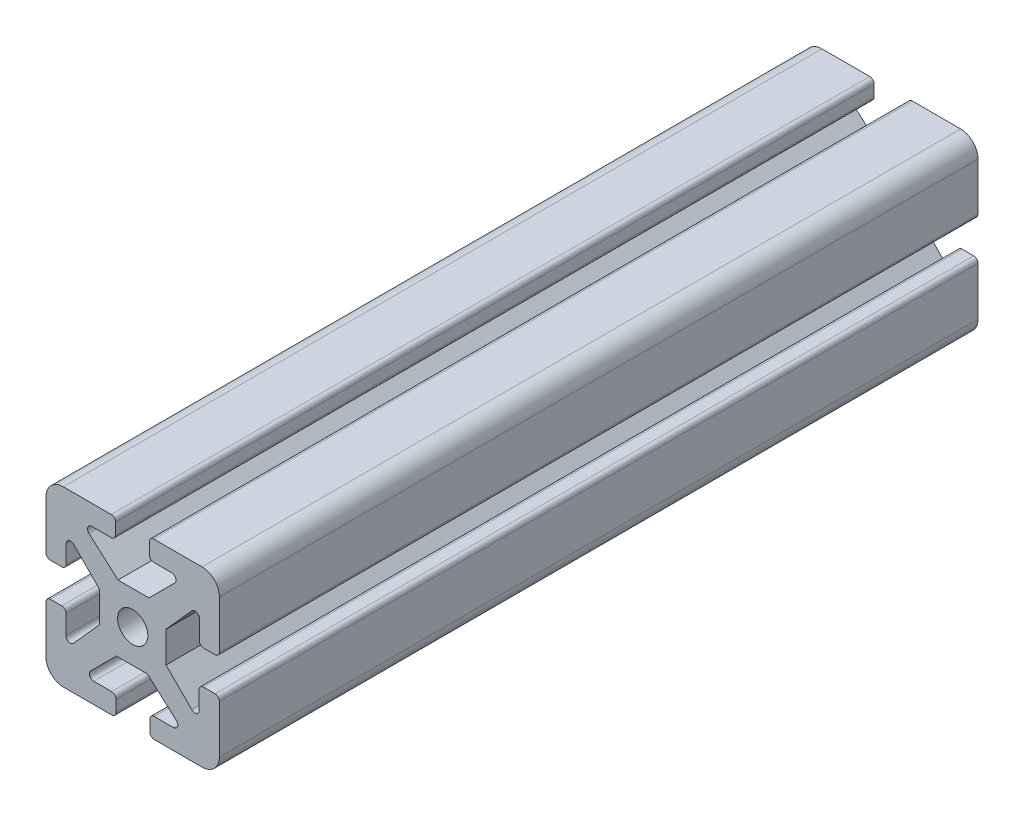
SolidWorks part; units mm, degrees
ref_plane "Front Plane" through (0, 0, 0) normal (0, 0, 1) x (1, 0, 0)
ref_plane "Top Plane" through (0, 0, 0) normal (0, 1, 0) x (1, 0, 0)
ref_plane "Right Plane" through (0, 0, 0) normal (1, 0, 0) x (0, 0, -1)
sketch "Sketch2" plane through (0, 0, 0) normal (0, 0, 1) x (1, 0, 0)
  line L0 (46.607, 139.3199) -> (233.0351, 139.3199) construction
  line L1 (0, 40) -> (40, 0) construction
  line L2 (0, 0) -> (40, 0) construction
  line L3 (0, 0) -> (0, 40) construction
  line L4 (0, 40) -> (40, 40) construction
  line L5 (40, 0) -> (40, 40) construction
  line L6 (0, 0) -> (40, 40) construction
  line L7 (19.4883, 27.6847) -> (23.7499, 27.6847)
  line L8 (23.7499, 27.6847) -> (29.6997, 33.625)
  line L9 (28.9931, 35.3327) -> (24.8456, 35.3327)
  line L10 (23.8456, 36.3327) -> (23.8456, 39)
  line L11 (24.8456, 40) -> (36, 40)
  line L12 (40, 36) -> (40, 24.9611)
  line L13 (39, 23.9611) -> (36.3883, 23.9611)
  line L14 (35.3883, 24.9611) -> (35.3883, 29.4086)
  line L15 (33.6417, 30.0739) -> (27.6847, 23.3888)
  line L16 (27.6847, 23.3888) -> (27.6847, 20.5117)
  line L17 (27.6847, 16.2501) -> (33.625, 10.3003)
  line L18 (30.0739, 6.3583) -> (23.3888, 12.3153)
  line L19 (27.6847, 20.5117) -> (27.6847, 16.2501)
  line L20 (35.3327, 11.0069) -> (35.3327, 15.1544)
  line L21 (36.3327, 16.1544) -> (39, 16.1544)
  line L22 (40, 15.1544) -> (40, 4)
  line L23 (36, 0) -> (24.9611, 0)
  line L24 (23.9611, 1) -> (23.9611, 3.6117)
  line L25 (24.9611, 4.6117) -> (29.4086, 4.6117)
  line L26 (23.3888, 12.3153) -> (20.5117, 12.3153)
  line L27 (16.2501, 12.3153) -> (10.3003, 6.375)
  line L28 (6.3583, 9.9261) -> (12.3153, 16.6112)
  line L29 (20.5117, 12.3153) -> (16.2501, 12.3153)
  line L30 (11.0069, 4.6673) -> (15.1544, 4.6673)
  line L31 (16.1544, 3.6673) -> (16.1544, 1)
  line L32 (15.1544, 0) -> (4, 0)
  line L33 (0, 4) -> (0, 15.0389)
  line L34 (1, 16.0389) -> (3.6117, 16.0389)
  line L35 (4.6117, 15.0389) -> (4.6117, 10.5914)
  line L36 (12.3153, 16.6112) -> (12.3153, 19.4883)
  line L37 (12.3153, 23.7499) -> (6.375, 29.6997)
  line L38 (9.9261, 33.6417) -> (16.6112, 27.6847)
  line L39 (12.3153, 19.4883) -> (12.3153, 23.7499)
  line L40 (4.6673, 28.9931) -> (4.6673, 24.8456)
  line L41 (3.6673, 23.8456) -> (1, 23.8456)
  line L42 (0, 24.8456) -> (0, 36)
  line L43 (4, 40) -> (15.0389, 40)
  line L44 (16.0389, 39) -> (16.0389, 36.3883)
  line L45 (15.0389, 35.3883) -> (10.5914, 35.3883)
  line L46 (16.6112, 27.6847) -> (19.4883, 27.6847)
  circle A1 centre (20, 20) radius 3.4925
  arc A2 (40, 24.9611) -> (39, 23.9611) centre (39, 24.9611) cw
  arc A3 (36.3883, 23.9611) -> (35.3883, 24.9611) centre (36.3883, 24.9611) cw
  arc A4 (24.8456, 35.3327) -> (23.8456, 36.3327) centre (24.8456, 36.3327) cw
  arc A5 (23.8456, 39) -> (24.8456, 40) centre (24.8456, 39) cw
  arc A6 (29.6997, 33.625) -> (28.9931, 35.3327) centre (28.9931, 34.3327) ccw
  arc A7 (35.3883, 29.4086) -> (33.6417, 30.0739) centre (34.3883, 29.4086) ccw
  arc A8 (40, 36) -> (36, 40) centre (36, 36) ccw
  arc A9 (35.3327, 15.1544) -> (36.3327, 16.1544) centre (36.3327, 15.1544) cw
  arc A10 (39, 16.1544) -> (40, 15.1544) centre (39, 15.1544) cw
  arc A11 (36, 0) -> (40, 4) centre (36, 4) ccw
  arc A12 (24.9611, 0) -> (23.9611, 1) centre (24.9611, 1) cw
  arc A13 (23.9611, 3.6117) -> (24.9611, 4.6117) centre (24.9611, 3.6117) cw
  arc A14 (29.4086, 4.6117) -> (30.0739, 6.3583) centre (29.4086, 5.6117) ccw
  arc A15 (33.625, 10.3003) -> (35.3327, 11.0069) centre (34.3327, 11.0069) ccw
  arc A16 (15.1544, 4.6673) -> (16.1544, 3.6673) centre (15.1544, 3.6673) cw
  arc A17 (16.1544, 1) -> (15.1544, 0) centre (15.1544, 1) cw
  arc A18 (0, 4) -> (4, 0) centre (4, 4) ccw
  arc A19 (0, 15.0389) -> (1, 16.0389) centre (1, 15.0389) cw
  arc A20 (3.6117, 16.0389) -> (4.6117, 15.0389) centre (3.6117, 15.0389) cw
  arc A21 (4.6117, 10.5914) -> (6.3583, 9.9261) centre (5.6117, 10.5914) ccw
  arc A22 (10.3003, 6.375) -> (11.0069, 4.6673) centre (11.0069, 5.6673) ccw
  arc A23 (4.6673, 24.8456) -> (3.6673, 23.8456) centre (3.6673, 24.8456) cw
  arc A24 (1, 23.8456) -> (0, 24.8456) centre (1, 24.8456) cw
  arc A25 (4, 40) -> (0, 36) centre (4, 36) ccw
  arc A26 (15.0389, 40) -> (16.0389, 39) centre (15.0389, 39) cw
  arc A27 (16.0389, 36.3883) -> (15.0389, 35.3883) centre (15.0389, 36.3883) cw
  arc A28 (10.5914, 35.3883) -> (9.9261, 33.6417) centre (10.5914, 34.3883) ccw
  arc A29 (6.375, 29.6997) -> (4.6673, 28.9931) centre (5.6673, 28.9931) ccw
  point P24 (40, 23.9611)
  point P31 (23.8456, 40)
  dimension "D1" = 40
  dimension "D3" = 1
  dimension "D4" = 4
  dimension "D2" = 40
  dimension "D5" = 4
extrude "Boss-Extrude1" add sketch "Sketch2" along normal blind 175
